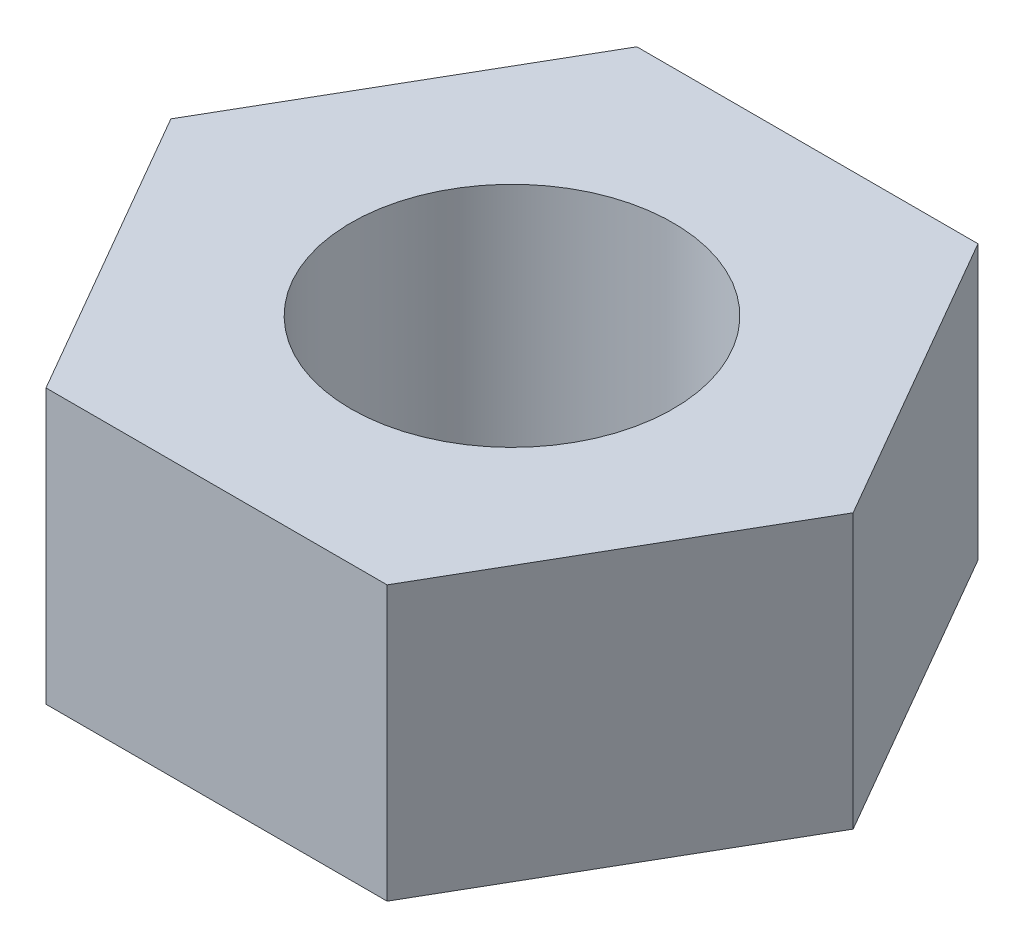
SolidWorks part; units mm, degrees
ref_plane "Front Plane" through (0, 0, 0) normal (0, 0, 1) x (1, 0, 0)
ref_plane "Top Plane" through (0, 0, 0) normal (0, 1, 0) x (1, 0, 0)
ref_plane "Right Plane" through (0, 0, 0) normal (1, 0, 0) x (0, 0, -1)
sketch "Sketch1" plane through (0, 0, 0) normal (0, 1, 0) x (1, 0, 0)
  line L1 (3.1754, 0) -> (1.5877, 2.75)
  line L2 (1.5877, 2.75) -> (-1.5877, 2.75)
  line L3 (-1.5877, 2.75) -> (-3.1754, 0)
  line L4 (-3.1754, 0) -> (-1.5877, -2.75)
  line L5 (-1.5877, -2.75) -> (1.5877, -2.75)
  line L6 (1.5877, -2.75) -> (3.1754, 0)
  circle A0 centre (0, 0) radius 2.75 construction
  circle A1 centre (0, 0) radius 1.5
  circle A2 centre (0, 0) radius 3.1754 construction
  dimension "D2" = 3
  dimension "D3" = 6.3509
  dimension "D1" = 5.5
extrude "Boss-Extrude1" add sketch "Sketch1" along normal blind 2.55
